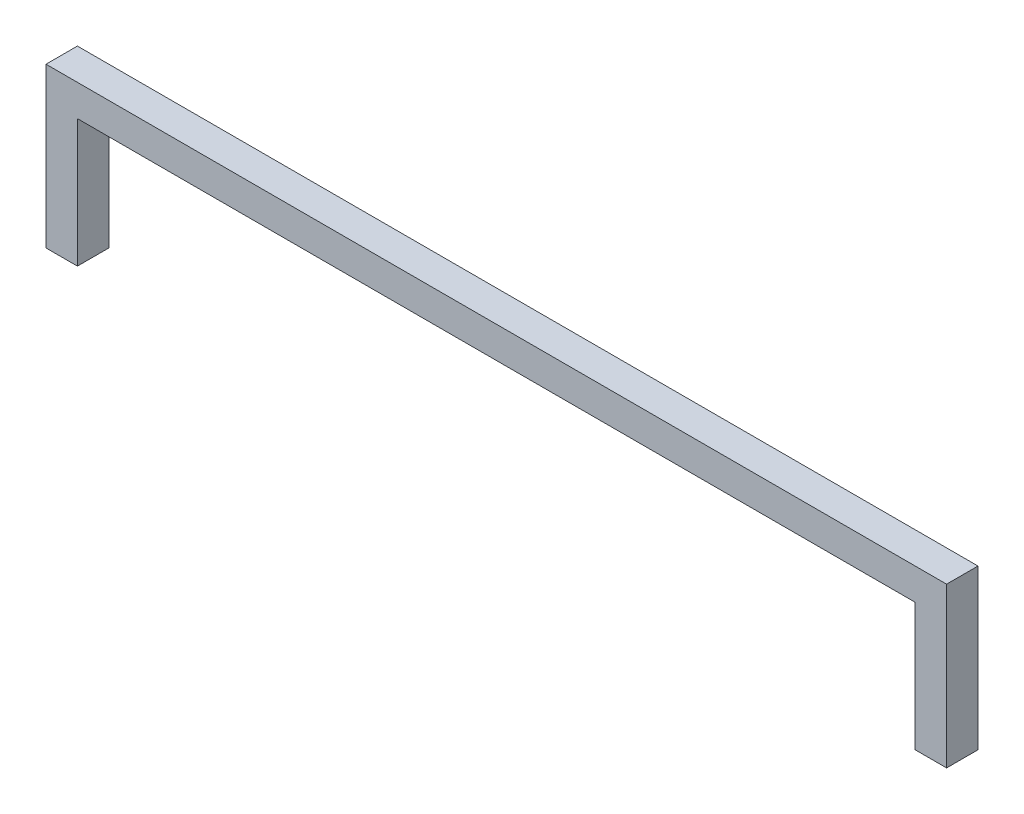
SolidWorks part; units mm, degrees
ref_plane "前视基准面" through (0, 0, 0) normal (0, 0, 1) x (1, 0, 0)
ref_plane "上视基准面" through (0, 0, 0) normal (0, 1, 0) x (1, 0, 0)
ref_plane "右视基准面" through (0, 0, 0) normal (1, 0, 0) x (0, 0, -1)
sketch "草图1" plane through (0, 0, 0) normal (0, 0, 1) x (1, 0, 0)
  line L0 (-30.6186, -6.7268) -> (-45.6186, -6.7268)
  line L1 (-45.6186, -6.7268) -> (-45.6186, 69.2732)
  line L2 (-45.6186, 69.2732) -> (384.3814, 69.2732)
  line L3 (384.3814, 69.2732) -> (384.3814, -6.7268)
  line L4 (384.3814, -6.7268) -> (369.3814, -6.7268)
  line L5 (369.3814, -6.7268) -> (369.3814, 54.2732)
  line L6 (369.3814, 54.2732) -> (-30.6186, 54.2732)
  line L7 (-30.6186, 54.2732) -> (-30.6186, -6.7268)
  dimension "D1" = 15
  dimension "D2" = 15
  dimension "D3" = 76
  dimension "D4" = 15
  dimension "D5" = 400
extrude "凸台-拉伸1" add sketch "草图1" along normal blind 15
